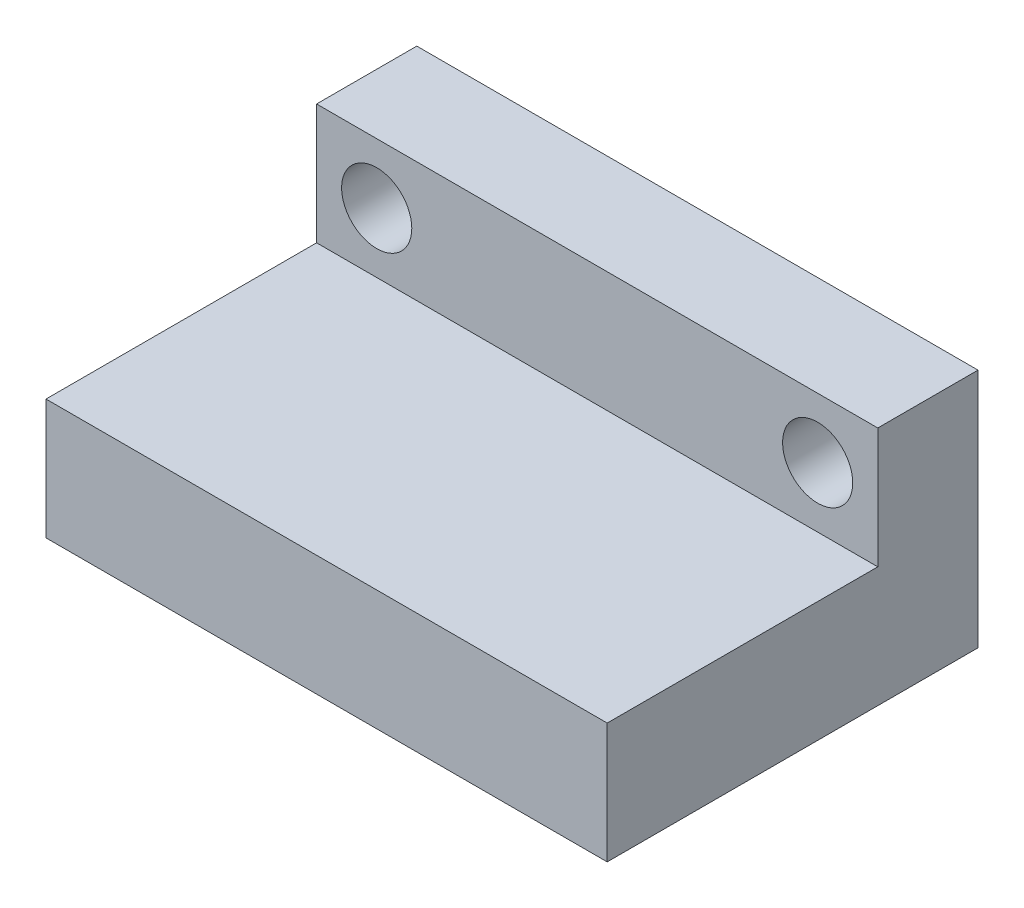
SolidWorks part; units mm, degrees
ref_plane "Front Plane" through (0, 0, 0) normal (0, 0, 1) x (1, 0, 0)
ref_plane "Top Plane" through (0, 0, 0) normal (0, 1, 0) x (1, 0, 0)
ref_plane "Right Plane" through (0, 0, 0) normal (1, 0, 0) x (0, 0, -1)
sketch "Sketch1" plane through (0, 0, 0) normal (0, 0, 1) x (1, 0, 0)
  line L1 (-14, 6) -> (14, 6)
  line L2 (-14, 6) -> (-14, -6)
  line L3 (-14, -6) -> (14, -6)
  line L4 (14, 6) -> (14, -6)
  line L5 (-14, 6) -> (14, -6) construction
  line L6 (-14, -6) -> (14, 6) construction
  point P0 (0, 0)
  dimension "D1" = 28
  dimension "D2" = 12
extrude "Boss-Extrude1" add sketch "Sketch1" along normal blind 5
sketch "Sketch2" plane through (0, 0, 5) normal (0, 0, 1) x (1, 0, 0)
  line L0 (14, -6) -> (14, 6) construction
  line L1 (-14, -6) -> (14, -6)
  line L2 (-14, -6) -> (-14, 0)
  line L3 (-14, 0) -> (14, 0)
  line L4 (14, -6) -> (14, 0)
extrude "Boss-Extrude2" add sketch "Sketch2" along normal blind 13.5
sketch "Sketch3" plane through (0, 0, 5) normal (0, 0, 1) x (1, 0, 0)
  line L0 (14, 6) -> (-14, 6) construction
  line L1 (-14, 6) -> (-14, 0) construction
  line L2 (0, 3.4227) -> (0, 0) construction
  line L3 (14, 0) -> (-14, 0) construction
  circle A0 centre (-11, 3) radius 1.75
  circle A1 centre (11, 3) radius 1.75
  dimension "D1" = 3.5
  dimension "D2" = 3
  dimension "D3" = 3
extrude "Cut-Extrude1" cut sketch "Sketch3" against normal through all
